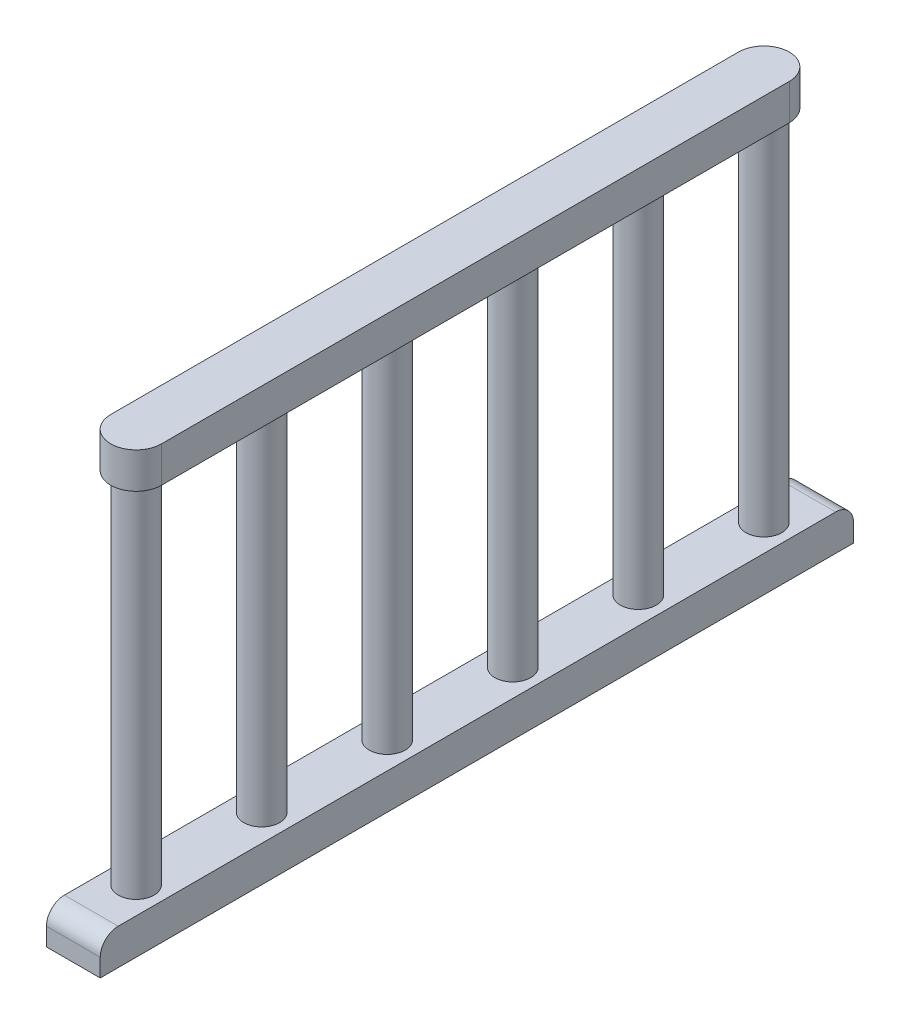
SolidWorks part; units mm, degrees
ref_plane "Front Plane" through (0, 0, 0) normal (0, 0, 1) x (1, 0, 0)
ref_plane "Top Plane" through (0, 0, 0) normal (0, 1, 0) x (1, 0, 0)
ref_plane "Right Plane" through (0, 0, 0) normal (1, 0, 0) x (0, 0, -1)
sketch "Sketch2" plane through (0, 0, 0) normal (0, 1, 0) x (1, 0, 0)
  line L0 (0, -12.024) -> (0, 987.976) construction
  line L1 (-1850, -12.024) -> (1850, -12.024) construction
  line L2 (1850, -12.024) -> (1700, -12.024)
  line L3 (-1850, -12.024) -> (-1700, -12.024)
  line L4 (-1850, -12.024) -> (-1850, 2087.976)
  line L5 (-1850, 2087.976) -> (-1700, 2087.976)
  line L6 (-1700, -12.024) -> (-1700, 2087.976)
  line L7 (1850, 2087.976) -> (1700, 2087.976)
  line L8 (1850, -12.024) -> (1850, 2087.976)
  line L9 (1700, -12.024) -> (1700, 2087.976)
  dimension "D1" = 1000
  dimension "D2" = 1850
  dimension "D3" = 2100
  dimension "D4" = 150
extrude "Boss-Extrude3" add sketch "Sketch2" along normal blind 100
ref_plane "Plane1" through (0, 100, 0) normal (0, 1, 0) x (1, 0, 0)
sketch "Sketch3" plane through (0, 100, 0) normal (0, 1, 0) x (1, 0, 0)
  line L0 (0, 0) -> (0, 2142.9852) construction
  line L1 (-1775, -12.024) -> (-1775, 162.976) construction
  line L2 (-1850, -12.024) -> (-1700, -12.024) construction
  circle A0 centre (-1775, 162.976) radius 50
  dimension "D2" = 100
  dimension "D1" = 175
extrude "Boss-Extrude4" add sketch "Sketch3" along normal blind 1000
pattern_linear "LPattern1" count 6 spacing 350 along (0, 0, -1) of "Boss-Extrude4"
ref_plane "Plane2" through (1700, 100, 12.024) normal (1, 0, 0) x (0, 0, -1)
sketch "Sketch5" plane through (0, 100, 0) normal (0, 1, 0) x (1, 0, 0)
  line L0 (1775, 2087.976) -> (1775, 1912.976) construction
  line L1 (1850, 2087.976) -> (1700, 2087.976) construction
  circle A0 centre (1775, 1912.976) radius 50
  dimension "D2" = 100
  dimension "D1" = 175
extrude "Boss-Extrude5" add sketch "Sketch5" along normal blind 1000
pattern_linear "LPattern2" count 6 spacing 350 along (0, 0, 1) of "Boss-Extrude5"
ref_plane "Plane3" through (0, 1100, 0) normal (0, 1, 0) x (1, 0, 0)
fillet "Fillet1" radius 50 1 edges at (-1775, 100, -2087.976)
fillet "Fillet2" radius 50 1 edges at (-1775, 100, 12.024)
fillet "Fillet3" radius 50 1 edges at (1775, 100, 12.024)
fillet "Fillet4" radius 50 1 edges at (1775, 100, -2087.976)
sketch "Sketch13" plane through (0, 1100, 0) normal (0, 1, 0) x (1, 0, 0)
  line L0 (-1775, 162.976) -> (-1775, 1912.976) construction
  line L1 (-1845.8383, 162.976) -> (-1845.8383, 1912.976)
  line L2 (-1704.1617, 162.976) -> (-1704.1617, 1912.976)
  line L3 (0, 0) -> (0, 2341.2867) construction
  line L4 (0, -605) -> (0, 605) construction
  line L5 (1775, 162.976) -> (1775, 1912.976) construction
  line L6 (1845.8383, 162.976) -> (1845.8383, 1912.976)
  line L7 (1704.1617, 162.976) -> (1704.1617, 1912.976)
  arc A0 (-1845.8383, 162.976) -> (-1704.1617, 162.976) centre (-1775, 162.976) ccw
  arc A1 (-1704.1617, 1912.976) -> (-1845.8383, 1912.976) centre (-1775, 1912.976) ccw
  arc A2 (1845.8383, 162.976) -> (1704.1617, 162.976) centre (1775, 162.976) cw
  arc A3 (1704.1617, 1912.976) -> (1845.8383, 1912.976) centre (1775, 1912.976) cw
  point P4 (-1775, 1037.976)
  point P16 (1775, 1037.976)
extrude "Boss-Extrude8" add sketch "Sketch13" along normal blind 100
sketch "Sketch14" plane through (0, 1100, 0) normal (0, 1, 0) x (1, 0, 0)
  line L1 (-1899.1526, 2186.8784) -> (-1093.8951, 2186.8784)
  line L2 (-1899.1526, 2186.8784) -> (-1899.1526, -316.0877)
  line L3 (-1899.1526, -316.0877) -> (-1093.8951, -316.0877)
  line L4 (-1093.8951, 2186.8784) -> (-1093.8951, -316.0877)
extrude "Cut-Extrude1" cut sketch "Sketch14" against normal blind 2000 and the other way blind 2000
